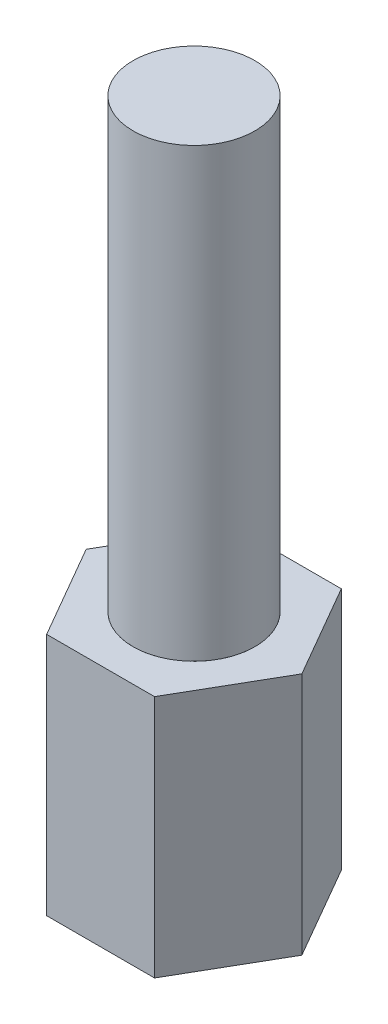
SolidWorks part; units mm, degrees
ref_plane "Front" through (0, 0, 0) normal (0, 0, 1) x (1, 0, 0)
ref_plane "Top" through (0, 0, 0) normal (0, 1, 0) x (1, 0, 0)
ref_plane "Right" through (0, 0, 0) normal (1, 0, 0) x (0, 0, -1)
sketch "草图1" plane through (0, 0, 0) normal (0, 1, 0) x (1, 0, 0)
  line L1 (-1.3279, 2.3) -> (-2.6558, 0)
  line L2 (-2.6558, 0) -> (-1.3279, -2.3)
  line L3 (-1.3279, -2.3) -> (1.3279, -2.3)
  line L4 (1.3279, -2.3) -> (2.6558, 0)
  line L5 (2.6558, 0) -> (1.3279, 2.3)
  line L6 (1.3279, 2.3) -> (-1.3279, 2.3)
  circle A0 centre (0, 0) radius 2.3 construction
  circle A1 centre (0, 0) radius 1.5 construction
  dimension "D2" = 3
  dimension "D1" = 4.6
extrude "凸台-拉伸1" add sketch "草图1" along normal blind 6
sketch "草图3" plane through (0, 6, 0) normal (0, 1, 0) x (1, 0, 0)
  circle A0 centre (0, 0) radius 1.5
  dimension "D1" = 3
extrude "凸台-拉伸2" add sketch "草图3" along normal blind 11
cosmetic thread "装饰螺纹线2" parameters "D2"=2
sketch "草图4" plane through (0, 0, 0) normal (0, -1, 0) x (1, 0, 0)
  circle A0 centre (0, 0) radius 1.5
  dimension "D1" = 3
extrude "切除-拉伸1" cut sketch "草图4" against normal up to surface (6 mm away) up to face at (0, 6, 1.5)
cosmetic thread "装饰螺纹线1" parameters "D2"=4
ref_plane "基准面1" through (0, 3, 0) normal (0, 1, 0) x (1, 0, 0)
